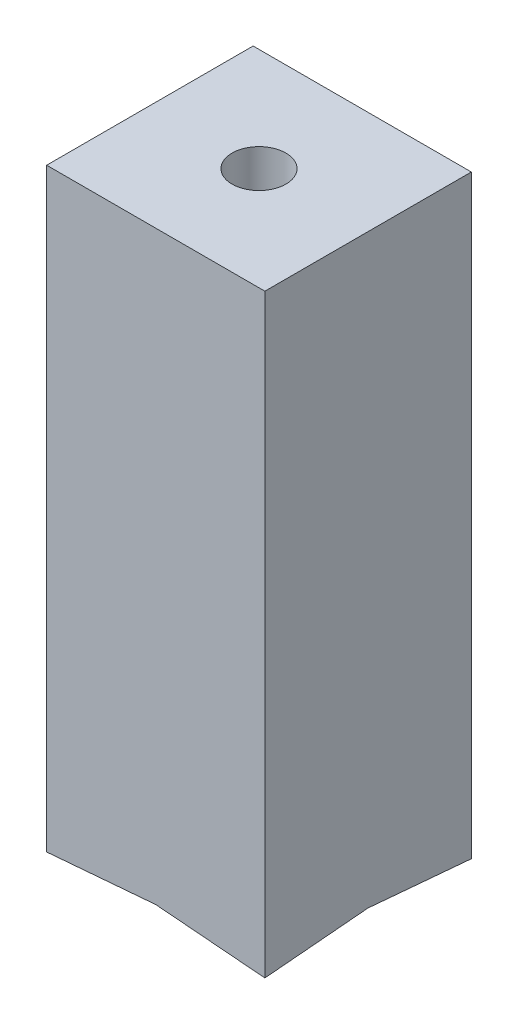
SolidWorks part; units mm, degrees
material "K110"
ref_plane "Front Plane" through (0, 0, 0) normal (0, 0, 1) x (1, 0, 0)
ref_plane "Top Plane" through (0, 0, 0) normal (0, 1, 0) x (1, 0, 0)
ref_plane "Right Plane" through (0, 0, 0) normal (1, 0, 0) x (0, 0, -1)
sketch "Sketch1" plane through (0, 0, 0) normal (0, 1, 0) x (1, 0, 0)
  line L1 (-10.125, -9.58) -> (10.125, -9.58)
  line L2 (-10.125, -9.58) -> (-10.125, 9.58)
  line L3 (-10.125, 9.58) -> (10.125, 9.58)
  line L4 (10.125, -9.58) -> (10.125, 9.58)
  line L5 (-10.125, -9.58) -> (10.125, 9.58) construction
  line L6 (-10.125, 9.58) -> (10.125, -9.58) construction
  point P0 (0, 0)
  dimension "D1" = 19.16
  dimension "D2" = 20.25
extrude "Boss-Extrude1" add sketch "Sketch1" against normal blind 55.2
sketch "Sketch5" plane through (10.125, 0, 0) normal (1, 0, 0) x (0, 0, -1)
  line L0 (-9.58, -55.2) -> (0, -54.3619)
  line L1 (0, -54.3619) -> (9.58, -55.2)
  line L2 (9.58, -55.2) -> (-9.58, -55.2)
  dimension "D1" = 5
extrude "Cut-Extrude2" cut sketch "Sketch5" against normal through all
sketch "Sketch6" plane through (0, 0, 9.58) normal (0, 0, 1) x (1, 0, 0)
  line L0 (-10.125, -55.2) -> (0, -54.3619)
  line L1 (-10.125, -54.3619) -> (10.125, -54.3619) construction
  line L2 (0, -54.3619) -> (10.125, -55.2)
  line L3 (10.125, -55.2) -> (-10.125, -55.2)
  dimension "D1" = 4.732
extrude "Cut-Extrude3" cut sketch "Sketch6" against normal through all
hole_wizard "M6 Tapped Hole1" positions "Sketch9" profile "Sketch8" tap size "M6" standard "ISO"
sketch "Sketch9" plane through (0, 0, 0) normal (0, 1, 0) x (1, 0, 0)
  point P0 (0, 0)
sketch "Sketch8" plane through (0, 0, 0) normal (1, 0, 0) x (0, 0, 1)
  line L0 (0, 0) -> (0, 16.5022)
  line L1 (0, 16.5022) -> (2.5, 15)
  line L2 (2.5, 15) -> (2.5, 0)
  line L5 (2.5, 0) -> (0, 0)
  line L10 (0, 16.5022) -> (-2.5, 15) construction
  line L11 (0, -6.35) -> (0, 107.95) construction
  dimension "Tap Drill Dia." = 5
  dimension "Tap Drill Depth" = 15
  dimension "Drill Angle" = 118
cosmetic thread "Hole Thread1"
